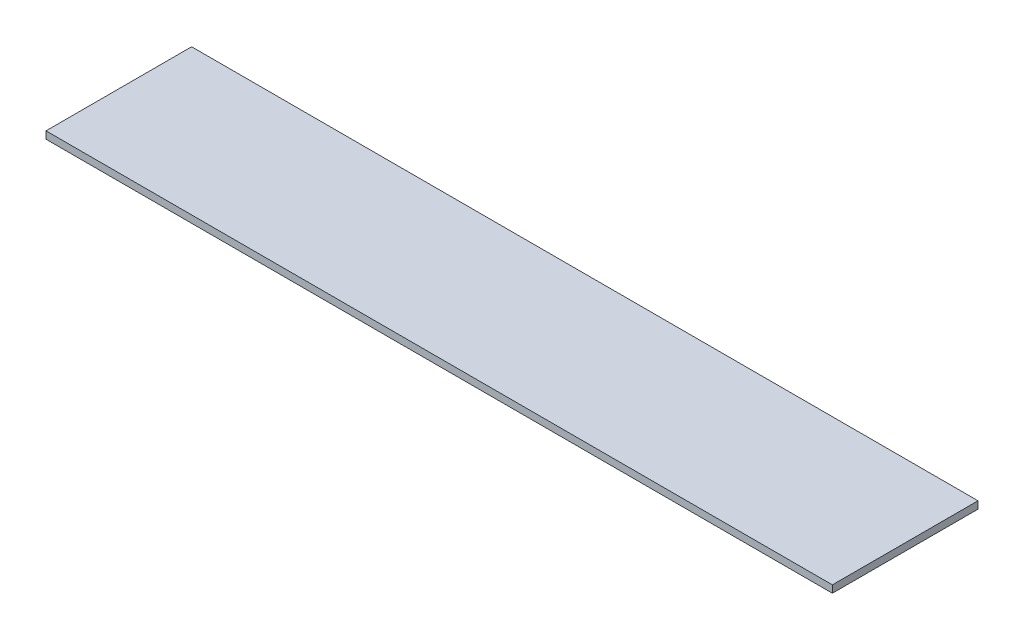
SolidWorks part; units mm, degrees
ref_plane "Front" through (0, 0, 0) normal (0, 0, 1) x (1, 0, 0)
ref_plane "Top" through (0, 0, 0) normal (0, 1, 0) x (1, 0, 0)
ref_plane "Right" through (0, 0, 0) normal (1, 0, 0) x (0, 0, -1)
sketch "Sketch1" plane through (0, 0, 0) normal (0, 1, 0) x (1, 0, 0)
  line L0 (0, 0) -> (2743.2, 0) construction
  line L1 (0, 254) -> (2743.2, 254)
  line L2 (0, 254) -> (0, -254)
  line L3 (0, -254) -> (2743.2, -254)
  line L4 (2743.2, 254) -> (2743.2, -254)
  dimension "D1" = 508
  dimension "D2" = 2743.2
extrude "Extrude1" add sketch "Sketch1" along normal blind 25.4
